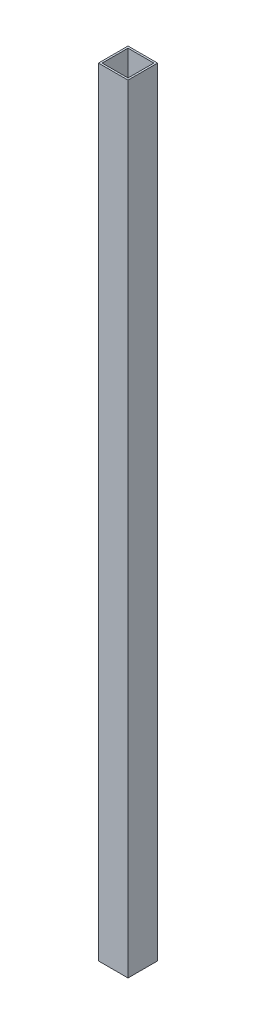
SolidWorks part; units mm, degrees
ref_plane "Front Plane" through (0, 0, 0) normal (0, 0, 1) x (1, 0, 0)
ref_plane "Top Plane" through (0, 0, 0) normal (0, 1, 0) x (1, 0, 0)
ref_plane "Right Plane" through (0, 0, 0) normal (1, 0, 0) x (0, 0, -1)
sketch "Sketch2" plane through (0, 0, 0) normal (0, 1, 0) x (1, 0, 0)
  line L0 (-8.3, 8.3) -> (8.3, 8.3)
  line L1 (-9.5, -9.5) -> (9.5, -9.5)
  line L2 (-9.5, -9.5) -> (-9.5, 9.5)
  line L3 (-9.5, 9.5) -> (9.5, 9.5)
  line L4 (9.5, -9.5) -> (9.5, 9.5)
  line L5 (-9.5, -9.5) -> (9.5, 9.5) construction
  line L6 (-9.5, 9.5) -> (9.5, -9.5) construction
  line L7 (8.3, -8.3) -> (8.3, 8.3)
  line L8 (-8.3, -8.3) -> (8.3, -8.3)
  line L9 (-8.3, -8.3) -> (-8.3, 8.3)
  point P0 (0, 0)
  dimension "D1" = 19
  dimension "D3" = 1.2
extrude "Boss-Extrude1" add sketch "Sketch2" along normal mid plane 500
